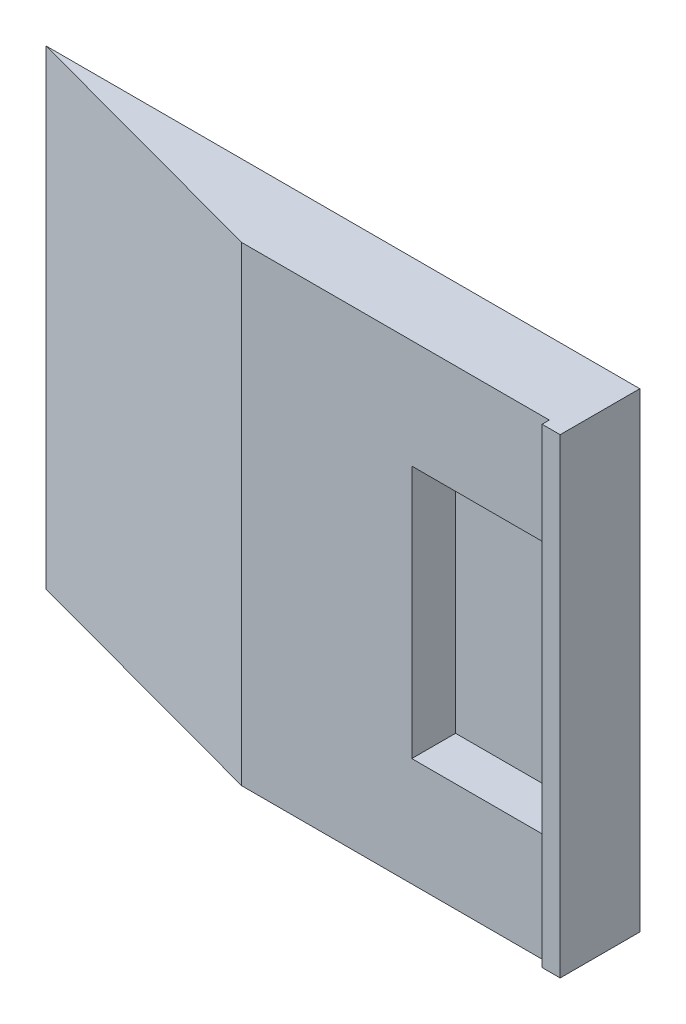
SolidWorks part; units mm, degrees
ref_plane "Front Plane" through (0, 0, 0) normal (0, 0, 1) x (1, 0, 0)
ref_plane "Top Plane" through (0, 0, 0) normal (0, 1, 0) x (1, 0, 0)
ref_plane "Right Plane" through (0, 0, 0) normal (1, 0, 0) x (0, 0, -1)
sketch "Sketch1" plane through (0, 0, 0) normal (0, 0, 1) x (1, 0, 0)
  line L0 (95, 175) -> (95, 325)
  line L1 (-95, -175) -> (95, -175)
  line L2 (-95, -175) -> (-95, 175)
  line L3 (-95, 175) -> (95, 175)
  line L4 (95, -175) -> (95, 175)
  line L5 (-95, -175) -> (95, 175) construction
  line L6 (-95, 175) -> (95, -175) construction
  line L7 (95, 325) -> (-330, 325)
  line L9 (95, -325) -> (-330, -325)
  line L10 (-330, 325) -> (-330, -325)
  line L11 (95, -175) -> (95, -325)
  line L12 (-95, 175) -> (-95, 325)
  point P0 (0, 0)
  dimension "D1" = 190
  dimension "D2" = 350
  dimension "D3" = 150
  dimension "D4" = 150
  dimension "D6" = 235
extrude "Boss-Extrude1" add sketch "Sketch1" along normal blind 60.5 contours L12 L3 L0 L7 | L2 L12 L7 L10 L9 L11 L1
sketch "Sketch3" plane through (95, 0, 0) normal (1, 0, 0) x (0, 0, -1)
  line L0 (0, -325) -> (-114.6236, -325)
  line L1 (-60.5, -325) -> (0, -325) construction
  line L2 (-60.5, 325) -> (0, 325) construction
  line L3 (0, 325) -> (-70.5, 325)
  line L4 (0, 325) -> (0, -325)
  line L5 (0, -325) -> (-70.5, -325)
  line L6 (-70.5, 325) -> (-70.5, -325)
  line L7 (0, 175) -> (0, 325) construction
  line M2 (0, 175) -> (0, 325)
  line M3 (0, 325) -> (-60.5, 325)
  line M4 (-60.5, 325) -> (-60.5, 175)
  line M5 (-60.5, 175) -> (0, 175)
  dimension "D1" = 70.5
extrude "Boss-Extrude2" add sketch "Sketch3" along normal blind 25 contours L3 L6 L5 L0 L4 M5 M4 | M5 M2 M3 M4
sketch "Sketch4" plane through (0, 0, 0) normal (0, 0, -1) x (-1, 0, 0)
  line L1 (-120, 325) -> (330, 325)
  line L2 (-120, 325) -> (-120, -325)
  line L3 (-120, -325) -> (330, -325)
  line L4 (330, 325) -> (330, -325)
extrude "Boss-Extrude3" add sketch "Sketch4" along normal blind 39.5
sketch "Sketch5" plane through (0, 0, -39.5) normal (0, 0, -1) x (-1, 0, 0)
  line L7 (330, 325) -> (700, 325)
  line L8 (330, 325) -> (330, -325)
  line L9 (330, -325) -> (700, -325)
  line L10 (700, 325) -> (700, -325)
  dimension "D2" = 370
sketch "Sketch8" plane through (0, 325, 0) normal (0, 1, 0) x (1, 0, 0)
  line L0 (-330, -60.5) -> (-700, 39.5)
  line L1 (-330, 39.5) -> (-700, 39.5) construction
  line L2 (-700, 39.5) -> (-330, 39.5)
  line L3 (-330, 39.5) -> (-330, -60.5)
extrude "Boss-Extrude4" add sketch "Sketch8" against normal up to surface (650 mm away) up to face at (-38.3333, -325, 30.5)
